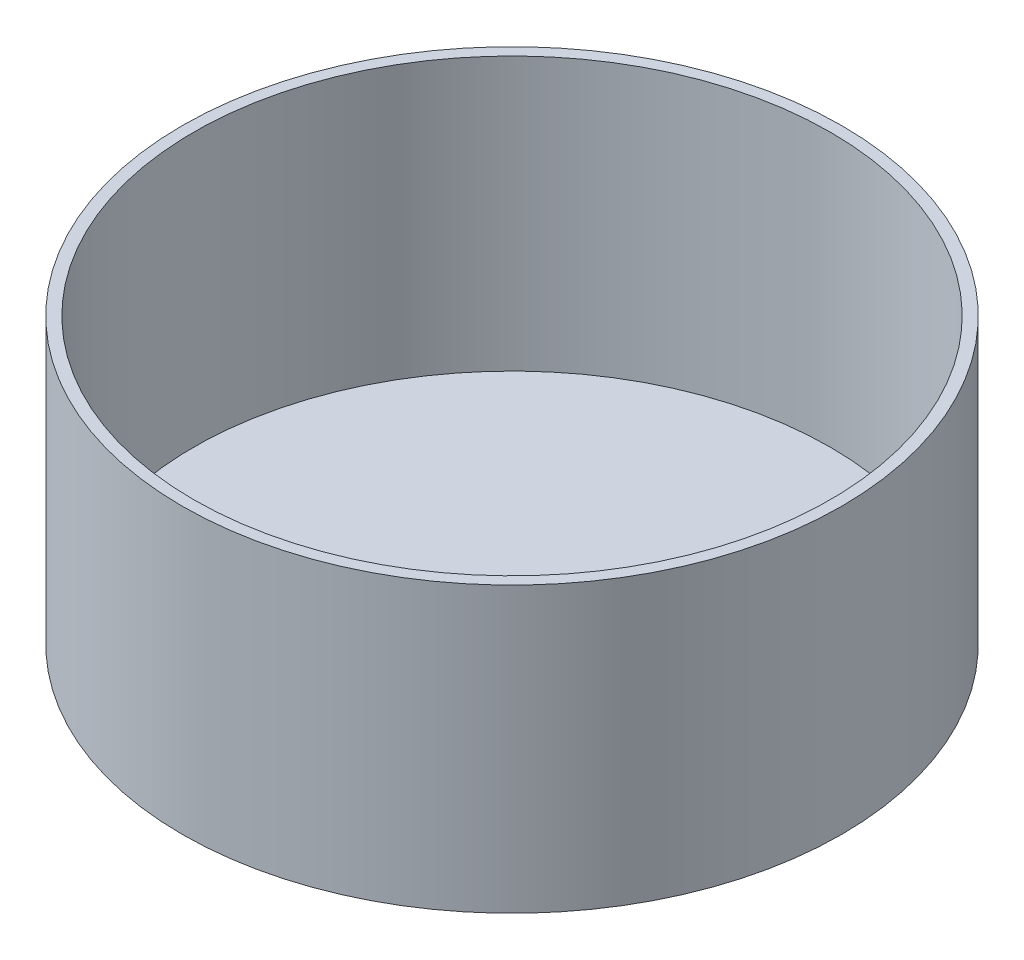
SolidWorks part; units mm, degrees
ref_plane "Plan de face" through (0, 0, 0) normal (0, 0, 1) x (1, 0, 0)
ref_plane "Plan de dessus" through (0, 0, 0) normal (0, 1, 0) x (1, 0, 0)
ref_plane "Plan de droite" through (0, 0, 0) normal (1, 0, 0) x (0, 0, -1)
sketch "Esquisse2" plane through (0, 0, 0) normal (0, 1, 0) x (1, 0, 0)
  circle A0 centre (0, 0) radius 58
extrude "Boss.-Extru.1" add sketch "Esquisse2" along normal blind 50 contours A0
sketch "Esquisse3" plane through (0, 50, 0) normal (0, 1, 0) x (1, 0, 0)
  circle A0 centre (0, 0) radius 56
extrude "Enlèv. mat.-Extru.1" cut sketch "Esquisse3" against normal blind 48
